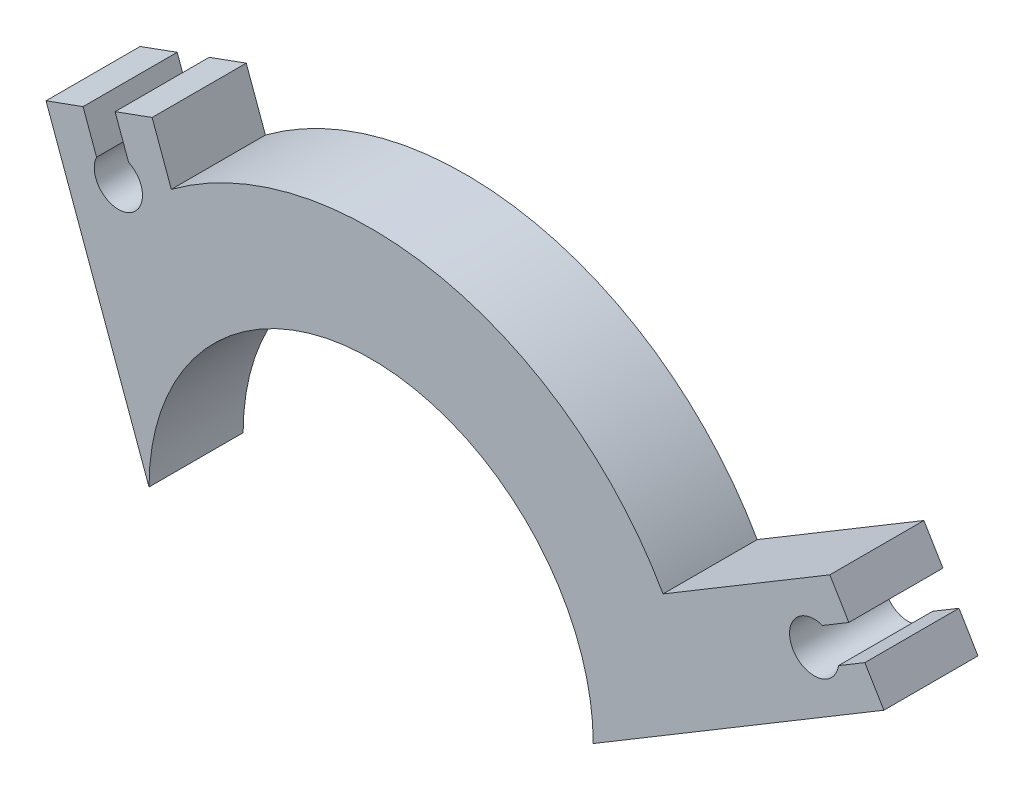
SolidWorks part; units mm, degrees
ref_plane "Front Plane" through (0, 0, 0) normal (0, 0, 1) x (1, 0, 0)
ref_plane "Top Plane" through (0, 0, 0) normal (0, 1, 0) x (1, 0, 0)
ref_plane "Right Plane" through (0, 0, 0) normal (1, 0, 0) x (0, 0, -1)
sketch "Sketch2" plane through (0, 0, 0) normal (0, 0, 1) x (1, 0, 0)
  line L0 (-3.7465, 0) -> (-5.484, 4.7736)
  line L1 (3.7465, 0) -> (8.6488, 2.9375)
  line L2 (8.6488, 2.9375) -> (8.3278, 3.4731)
  line L3 (7.7367, 4.4597) -> (4.9238, 2.7741)
  line L4 (-5.484, 4.7736) -> (-4.8589, 5.0011)
  line L5 (-3.6938, 5.4252) -> (-3.3704, 4.5365)
  line L6 (-5.2696, 6.9696) -> (-3.4319, 1.9204) construction
  line L7 (-4.8589, 5.0011) -> (-4.6315, 4.3761)
  line L8 (-4.3189, 5.1977) -> (-4.0914, 4.5727)
  line L9 (-4.3189, 5.1977) -> (-3.6938, 5.4252)
  line L10 (8.1927, 3.6986) -> (7.4726, 3.2671) construction
  line L11 (8.3278, 3.4731) -> (7.883, 3.2065)
  line L12 (8.0576, 3.9241) -> (7.6127, 3.6575)
  line L13 (8.0576, 3.9241) -> (7.7367, 4.4597)
  arc A0 (3.7465, 0) -> (-3.7465, 0) centre (0, 0) ccw
  arc A1 (4.9238, 2.7741) -> (-3.3704, 4.5365) centre (0, 0) ccw
  circle A2 centre (0, 0) radius 5.6515 construction
  circle A3 centre (0, 0) radius 3.7465 construction
  arc A4 (-4.6315, 4.3761) -> (-4.0914, 4.5727) centre (-4.2631, 4.2044) ccw
  arc A5 (7.6127, 3.6575) -> (7.883, 3.2065) centre (7.4726, 3.2671) ccw
  dimension "D1" = 7.493
  dimension "D5" = 0.8128
  dimension "D3" = 5.08
  dimension "D4" = 5.715
  dimension "D6" = 1.905
  dimension "D7" = 0.8395
  dimension "D8" = 0.8872
  dimension "D9" = 0.8872
  dimension "D2" = 1.905
extrude "Boss-Extrude1" add sketch "Sketch2" along normal blind 1.5875
equation "\"D8@Sketch2\" = \"D9@Sketch2\""
